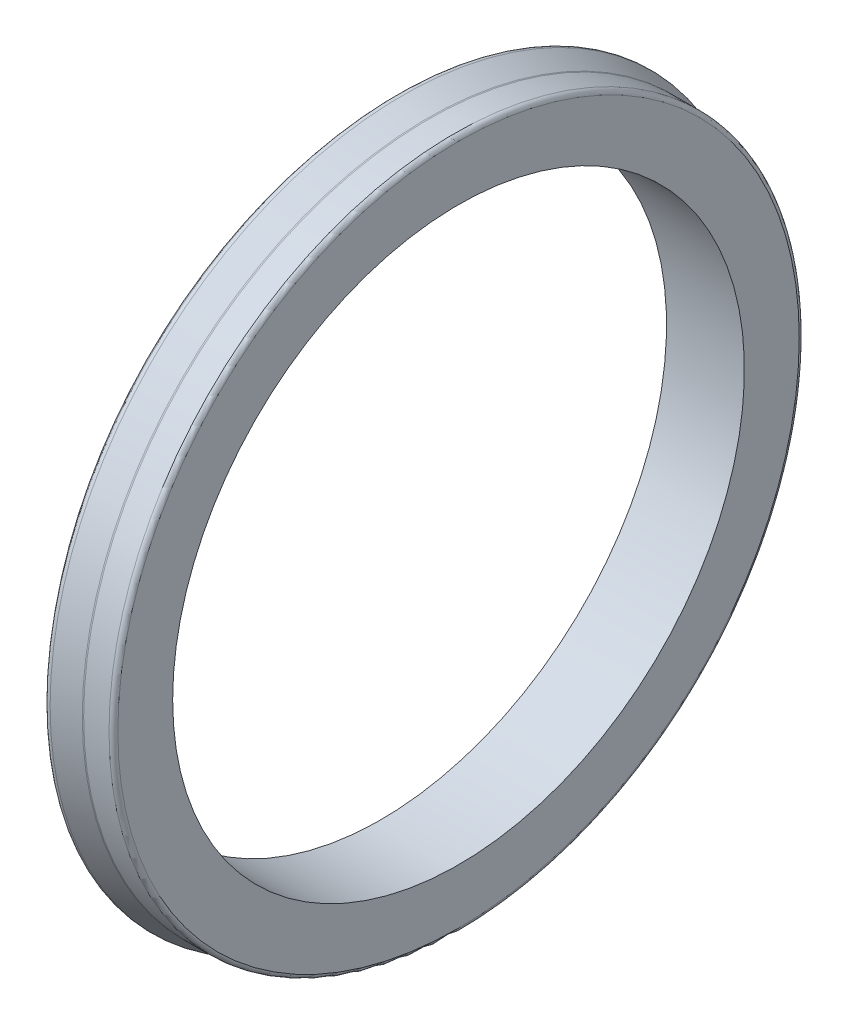
SolidWorks part; units mm, degrees
ref_plane "Alzado" through (0, 0, 0) normal (0, 0, 1) x (1, 0, 0)
ref_plane "Planta" through (0, 0, 0) normal (0, 1, 0) x (1, 0, 0)
ref_plane "Vista lateral" through (0, 0, 0) normal (1, 0, 0) x (0, 0, -1)
sketch "Croquis1" plane through (0, 0, 0) normal (0, 1, 0) x (1, 0, 0)
  line L0 (0, 0) -> (0, 16) construction
  line L1 (0, 0) -> (0, -16) construction
  line L2 (0, 0) -> (39.0941, 0) construction
  line L3 (168.2208, 380.5874) -> (1078.8874, 380.5874) construction
  line L4 (-6.299, 12.9508) -> (-2.772, 12.9508)
  line L5 (-2.772, 12.9508) -> (-2.772, 15.4349)
  line L6 (-2.972, 15.6349) -> (-4.1195, 15.6349)
  line L7 (-4.1741, 15.6425) -> (-5.3092, 15.9646)
  line L8 (-5.5171, 15.9006) -> (-5.7581, 15.6129)
  line L9 (-5.6705, 15.2956) -> (-4.215, 14.7888)
  line L10 (-4.2499, 14.4023) -> (-6.1299, 14.1085)
  line L11 (-6.299, 13.9109) -> (-6.299, 12.9508)
  arc A0 (-6.299, 13.9109) -> (-6.1299, 14.1085) centre (-6.099, 13.9109) cw
  arc A1 (-4.1741, 15.6425) -> (-4.1195, 15.6349) centre (-4.1195, 15.8349) ccw
  arc A2 (-5.5171, 15.9006) -> (-5.3092, 15.9646) centre (-5.3638, 15.7722) cw
  arc A3 (-5.7581, 15.6129) -> (-5.6705, 15.2956) centre (-5.6048, 15.4845) ccw
  arc A4 (-4.215, 14.7888) -> (-4.2499, 14.4023) centre (-4.2807, 14.5999) cw
  arc A5 (-2.772, 15.4349) -> (-2.972, 15.6349) centre (-2.972, 15.4349) ccw
  dimension "D3" = 0.2
  dimension "D4" = 0.2
  dimension "D1" = 16
  dimension "D2" = 16
revolve "Revolución1" add sketch "Croquis1" angle 360 about L2
